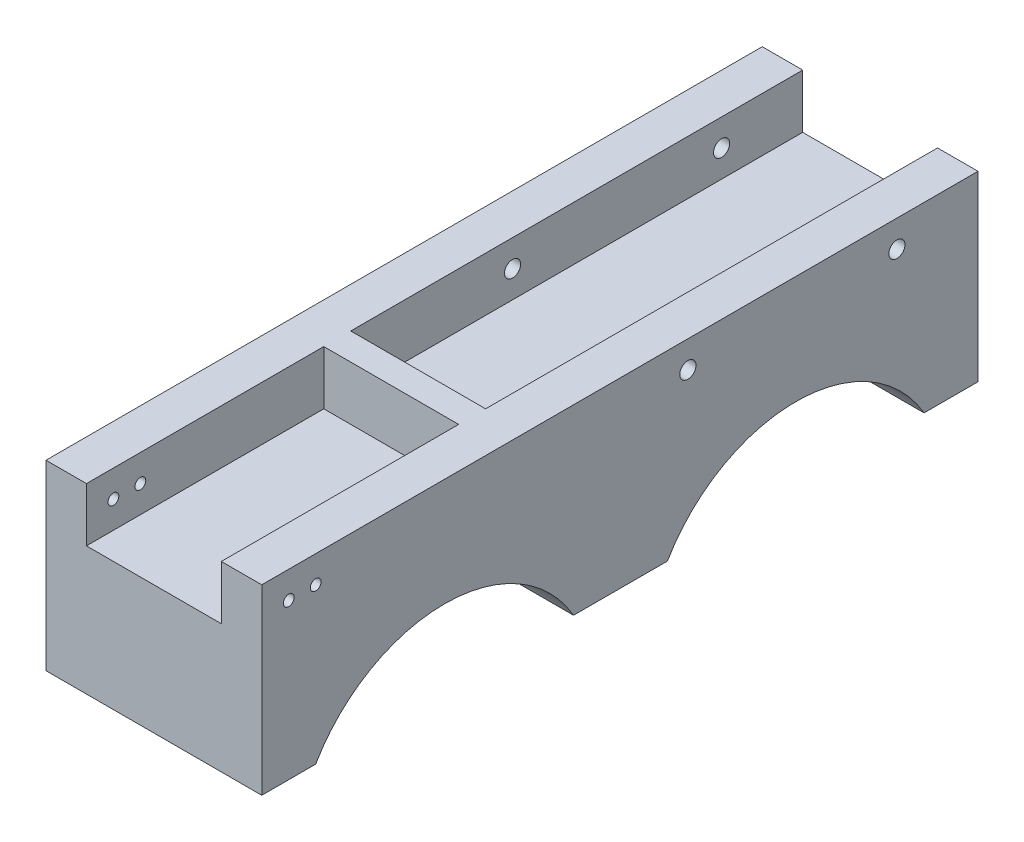
SolidWorks part; units mm, degrees
ref_plane "Спереди" through (0, 0, 0) normal (0, 0, 1) x (1, 0, 0)
ref_plane "Сверху" through (0, 0, 0) normal (0, 1, 0) x (1, 0, 0)
ref_plane "Справа" through (0, 0, 0) normal (1, 0, 0) x (0, 0, -1)
sketch "Эскиз2" plane through (0, 0, 0) normal (1, 0, 0) x (0, 0, -1)
  line L0 (-47.8046, 27.6) -> (0, 0) construction
  line L1 (0, 0) -> (47.8046, 27.6) construction
  line L2 (-47.8046, 27.6) -> (-67.8046, 27.6)
  line L3 (-67.8046, 27.6) -> (-67.8046, 95.2)
  line L7 (-10, 54.2866) -> (-10, 45.2)
  line L8 (-10, 45.2) -> (10, 45.2)
  line L9 (10, 45.2) -> (10, 54.2866)
  line L10 (0, 0) -> (0, 95.2) construction
  line L11 (55.2, 0) -> (75.2, 0) construction
  line L12 (-67.8046, 95.2) -> (197.7735, 95.2)
  line L14 (47.8046, 27.6) -> (82.6265, 27.6)
  line L15 (177.7735, 27.6) -> (197.7735, 27.6)
  line L16 (197.7735, 27.6) -> (197.7735, 95.2)
  line L19 (130.2, 0) -> (130.2, 95.2) construction
  line L21 (120.2, 54.0833) -> (120.2, 45.2)
  line L22 (120.2, 45.2) -> (140.2, 45.2)
  line L23 (140.2, 45.2) -> (140.2, 54.0833)
  arc A0 (-47.8046, 27.6) -> (-10, 54.2866) centre (0, 0) cw
  arc A1 (10, 54.2866) -> (47.8046, 27.6) centre (0, 0) cw
  arc A2 (47.8046, 27.6) -> (-47.8046, 27.6) centre (0, 0) ccw construction
  circle A5 centre (-47.8046, 85.2) radius 2
  circle A6 centre (-57.8046, 85.2) radius 2
  arc A7 (10, 54.2866) -> (55.2, 0) centre (0, 0) cw construction
  arc A8 (75.2, 0) -> (120.2, 54.0833) centre (130.2, 0) cw construction
  arc A11 (82.6265, 27.6) -> (120.2, 54.0833) centre (130.2, 0) cw
  arc A12 (140.2, 54.0833) -> (177.7735, 27.6) centre (130.2, 0) cw
  arc A13 (140.2, 54.0833) -> (185.2, 0) centre (130.2, 0) cw construction
  circle A15 centre (90.2, 85.2) radius 3
  circle A16 centre (167.7, 85.2) radius 3
  point P4 (0, 45.2)
  point P14 (0, 55.2)
  dimension "D1" = 55.2
  dimension "D2" = 120
  dimension "D6" = 55
  dimension "D7" = 6
  dimension "D11" = 4
  dimension "D8" = 20
  dimension "D14" = 10
  dimension "D3" = 20
  dimension "D10" = 20
  dimension "D9" = 37.5
  dimension "D4" = 20
  dimension "D5" = 10
  dimension "D12" = 10
  dimension "D13" = 10
  dimension "D15" = 40
  dimension "D16" = 50
  dimension "D18" = 10
extrude "Бобышка-Вытянуть1" add sketch "Эскиз2" along normal blind 80
sketch "Эскиз6" plane through (0, 45.2, 0) normal (0, -1, 0) x (1, 0, 0)
  line L0 (0, 0) -> (80, 0) construction
  line L1 (80, 10) -> (80, -10) construction
  line L3 (15, -10) -> (0, -10)
  line L4 (15, -10) -> (15, 10)
  line L5 (15, 10) -> (0, 10)
  line L6 (0, -10) -> (0, 10)
  line L7 (15, -10) -> (0, 10) construction
  line L8 (15, 10) -> (0, -10) construction
  line L9 (65, -10) -> (80, -10)
  line L10 (65, -10) -> (65, 10)
  line L11 (65, 10) -> (80, 10)
  line L12 (80, -10) -> (80, 10)
  line L13 (65, -10) -> (80, 10) construction
  line L14 (65, 10) -> (80, -10) construction
  point P5 (7.5, 0)
  point P10 (72.5, 0)
  dimension "D1" = 15
extrude "Вырез-Вытянуть2" cut sketch "Эскиз6" against normal up to surface (9.0866 mm away)
sketch "Эскиз7" plane through (0, 0, -197.7735) normal (0, 0, -1) x (-1, 0, 0)
  line L0 (-80, 95.2) -> (0, 95.2) construction
  line L1 (-65, 95.2) -> (-15, 95.2)
  line L2 (-65, 95.2) -> (-65, 75.2)
  line L3 (-65, 75.2) -> (-15, 75.2)
  line L4 (-15, 95.2) -> (-15, 75.2)
  line L5 (-40, 27.6) -> (-40, 95.2) construction
  line L6 (-80, 27.6) -> (0, 27.6) construction
  point P10 (-40, 95.2)
  dimension "D1" = 50
  dimension "D2" = 20
extrude "Вырез-Вытянуть3" cut sketch "Эскиз7" against normal up to surface (265.5781 mm away) up to face at (40, 61.4, 67.8046)
sketch "Эскиз8" plane through (0, 45.2, 0) normal (0, -1, 0) x (1, 0, 0)
  line L0 (80, -140.2) -> (0, -140.2) construction
  line L1 (0, -120.2) -> (15, -120.2)
  line L2 (0, -120.2) -> (0, -140.2)
  line L3 (0, -140.2) -> (15, -140.2)
  line L4 (15, -120.2) -> (15, -140.2)
  line L5 (80, -140.2) -> (0, -140.2) construction
  line L6 (80, -120.2) -> (65, -120.2)
  line L7 (80, -120.2) -> (80, -140.2)
  line L8 (80, -140.2) -> (65, -140.2)
  line L9 (65, -120.2) -> (65, -140.2)
  dimension "D1" = 15
  dimension "D2" = 15
extrude "Вырез-Вытянуть4" cut sketch "Эскиз8" against normal up to surface (8.8833 mm away)
sketch "Эскиз9" plane through (0, 75.2, 0) normal (0, 1, 0) x (1, 0, 0)
  line L0 (15, -67.8046) -> (15, 197.7735) construction
  line L1 (15, 20.2) -> (65, 20.2)
  line L2 (15, 20.2) -> (15, 30.2)
  line L3 (15, 30.2) -> (65, 30.2)
  line L4 (65, 20.2) -> (65, 30.2)
  line L5 (65, -67.8046) -> (65, 197.7735) construction
  line L7 (65, 120.2) -> (65, 140.2) construction
  point P10 (65, 130.2)
  dimension "D1" = 100
  dimension "D2" = 10
extrude "Бобышка-Вытянуть2" add sketch "Эскиз9" along normal up to surface (20 mm away) up to face at (72.5, 95.2, -64.9845)
